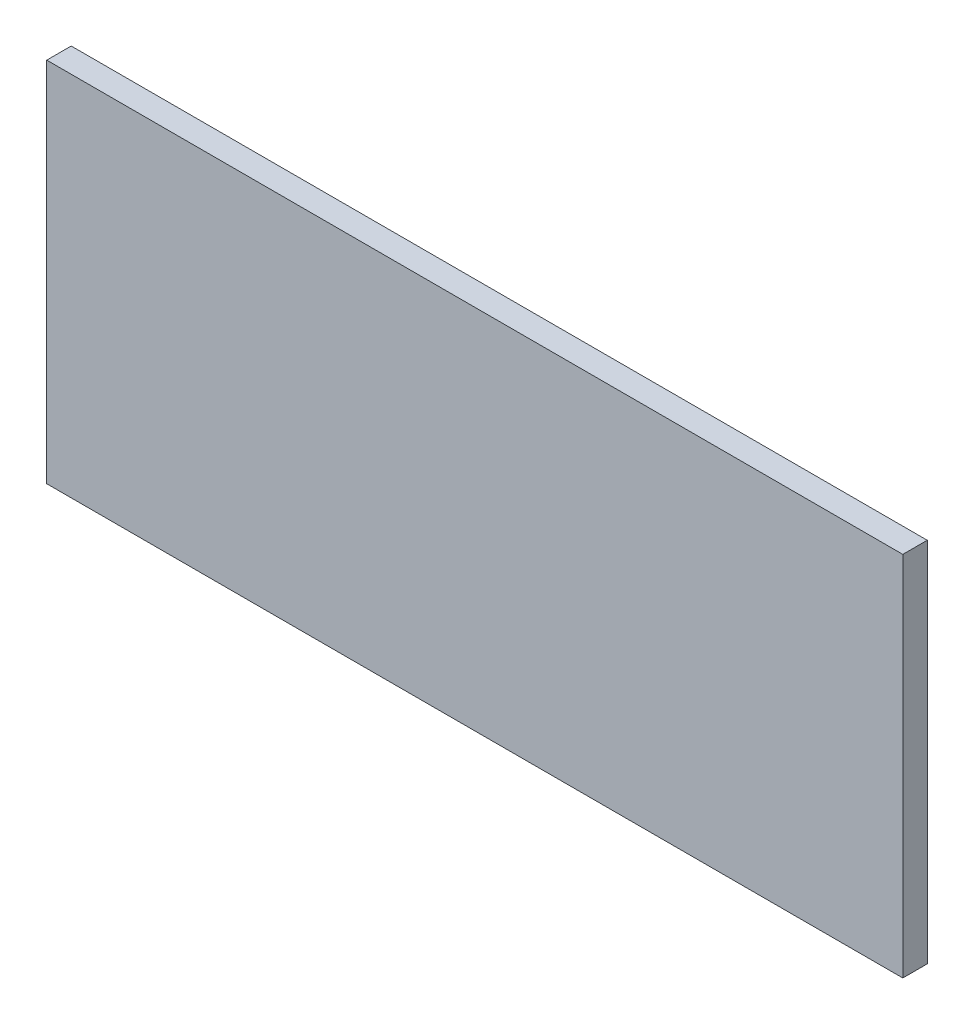
SolidWorks part; units mm, degrees
ref_plane "Ön Düzlem" through (0, 0, 0) normal (0, 0, 1) x (1, 0, 0)
ref_plane "Üst Düzlem" through (0, 0, 0) normal (0, 1, 0) x (1, 0, 0)
ref_plane "Sağ Düzlem" through (0, 0, 0) normal (1, 0, 0) x (0, 0, -1)
sketch "Çizim1" plane through (0, 0, 0) normal (0, 0, 1) x (1, 0, 0)
  line L1 (0, 0) -> (-140, 0)
  line L2 (0, 0) -> (0, 60)
  line L3 (0, 60) -> (-140, 60)
  line L4 (-140, 0) -> (-140, 60)
  dimension "D1" = 60
  dimension "D2" = 140
extrude "Yükseklik-Ekstrüzyon1" add sketch "Çizim1" along normal blind 4
